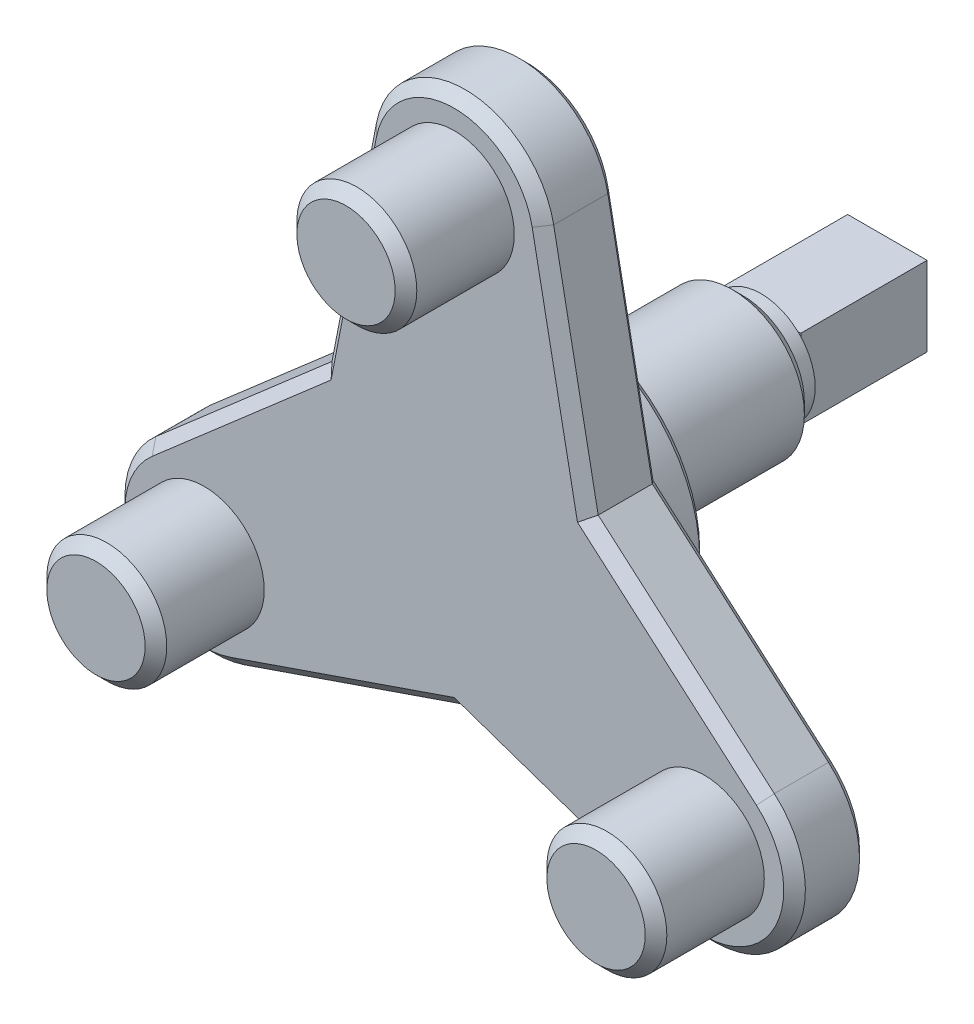
SolidWorks part; units mm, degrees
ref_plane "Piano frontale" through (0, 0, 0) normal (0, 0, 1) x (1, 0, 0)
ref_plane "Piano superiore" through (0, 0, 0) normal (0, 1, 0) x (1, 0, 0)
ref_plane "Piano destro" through (0, 0, 0) normal (1, 0, 0) x (0, 0, -1)
sketch "Schizzo1" plane through (0, 0, 0) normal (0, 0, 1) x (1, 0, 0)
  line L1 (1.1, -1.1) -> (-1.1, -1.1)
  line L2 (1.1, -1.1) -> (1.1, 1.1)
  line L3 (1.1, 1.1) -> (-1.1, 1.1)
  line L4 (-1.1, -1.1) -> (-1.1, 1.1)
  line L5 (1.1, -1.1) -> (-1.1, 1.1) construction
  line L6 (1.1, 1.1) -> (-1.1, -1.1) construction
  point P0 (0, 0)
  dimension "D1" = 2.2
  dimension "D2" = 2.2
extrude "Estrusione-Estrusione1" add sketch "Schizzo1" along normal blind 3.5
sketch "Schizzo2" plane through (0, 0, 3.5) normal (0, 0, 1) x (1, 0, 0)
  circle A0 centre (0, 0) radius 1.5
  dimension "D1" = 3
extrude "Estrusione-Estrusione2" add sketch "Schizzo2" along normal blind 0.5
sketch "Schizzo3" plane through (0, 0, 4) normal (0, 0, 1) x (1, 0, 0)
  circle A0 centre (0, 0) radius 2
  dimension "D1" = 4
extrude "Estrusione-Estrusione3" add sketch "Schizzo3" along normal blind 5
sketch "Schizzo4" plane through (0, 0, 9) normal (0, 0, 1) x (1, 0, 0)
  circle A0 centre (0, 0) radius 4
  dimension "D1" = 8
extrude "Estrusione-Estrusione4" add sketch "Schizzo4" along normal blind 1
sketch "Schizzo11" plane through (0, 0, 10) normal (0, 0, 1) x (1, 0, 0)
  line L0 (0, 0) -> (0, 8) construction
  line L1 (-3.688, 2.1292) -> (-2.4541, 8.477)
  line L2 (2.4541, 8.477) -> (3.688, 2.1292)
  line L3 (6.1143, -6.3638) -> (0, -4.2585)
  line L4 (3.688, 2.1292) -> (8.5684, -2.1132)
  line L5 (-8.5684, -2.1132) -> (-3.688, 2.1292)
  line L6 (0, -4.2585) -> (-6.1143, -6.3638)
  circle A0 centre (0, 0) radius 8 construction
  arc A1 (2.4541, 8.477) -> (-2.4541, 8.477) centre (0, 8) ccw
  arc A2 (6.1143, -6.3638) -> (8.5684, -2.1132) centre (6.9282, -4) ccw
  arc A3 (-8.5684, -2.1132) -> (-6.1143, -6.3638) centre (-6.9282, -4) ccw
  point P3 (0, 0)
  point P9 (0, 0)
  point P10 (0, 0)
  point P11 (0, 0)
  point P13 (0, 0)
  dimension "D1" = 16
  dimension "D2" = 5
  dimension "D3" = 22
  dimension "D4" = 3
extrude "Estrusione-Estrusione7" add sketch "Schizzo11" along normal blind 2
sketch "Schizzo12" plane through (0, 0, 12) normal (0, 0, 1) x (1, 0, 0)
  circle A0 centre (0, 8) radius 1.6615
  arc A1 (2.4541, 8.477) -> (-2.4541, 8.477) centre (0, 8) ccw construction
  circle A2 centre (0, 0) radius 8 construction
  circle A3 centre (0, 0) radius 8 construction
  circle A4 centre (6.9282, -4) radius 1.6615
  circle A5 centre (0, 0) radius 8 construction
  circle A6 centre (-6.9282, -4) radius 1.6615
  dimension "D1" = 3.3229
  dimension "D2" = 3
extrude "Estrusione-Estrusione8" add sketch "Schizzo12" along normal blind 3
chamfer "Smusso4" distance 0.2 angle 45 10 edges at (4, 0, 9) (6.1282, 0.008, 10) (9.0933, -5.25, 10) (3.0571, -5.3111, 10) (-3.0571, -5.3111, 10) (3.071, 5.3031, 10) (-9.0933, -5.25, 10) (0, 10.5, 10) (-6.1282, 0.008, 10) (-3.071, 5.3031, 10)
chamfer "Smusso5" distance 0.3 angle 45 13 edges at (-5.2667, -4, 15) (8.5897, -4, 15) (3.0571, -5.3111, 12) (9.0933, -5.25, 12) (6.1282, 0.008, 12) (1.6615, 8, 15) (-3.0571, -5.3111, 12) (3.071, 5.3031, 12) (-9.0933, -5.25, 12) (0, 10.5, 12) (-6.1282, 0.008, 12) (-3.071, 5.3031, 12) (2, 0, 4)
